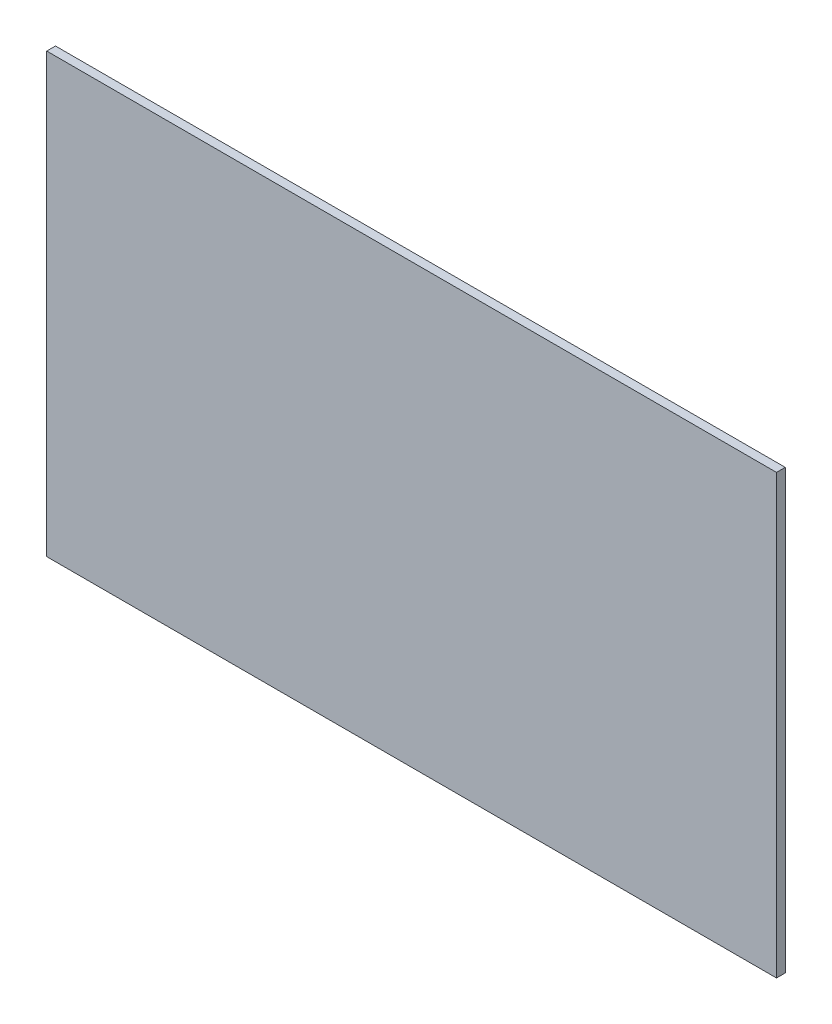
SolidWorks part; units mm, degrees
ref_plane "Спереди" through (0, 0, 0) normal (0, 0, 1) x (1, 0, 0)
ref_plane "Сверху" through (0, 0, 0) normal (0, 1, 0) x (1, 0, 0)
ref_plane "Справа" through (0, 0, 0) normal (1, 0, 0) x (0, 0, -1)
sketch "Эскиз1" plane through (0, 0, 0) normal (0, 0, 1) x (1, 0, 0)
  line L1 (-104.4541, 64.6168) -> (145.5459, 64.6168)
  line L2 (-104.4541, 64.6168) -> (-104.4541, -85.3832)
  line L3 (-104.4541, -85.3832) -> (145.5459, -85.3832)
  line L4 (145.5459, 64.6168) -> (145.5459, -85.3832)
  dimension "D1" = 250
  dimension "D2" = 150
extrude "Бобышка-Вытянуть1" add sketch "Эскиз1" along normal blind 3
